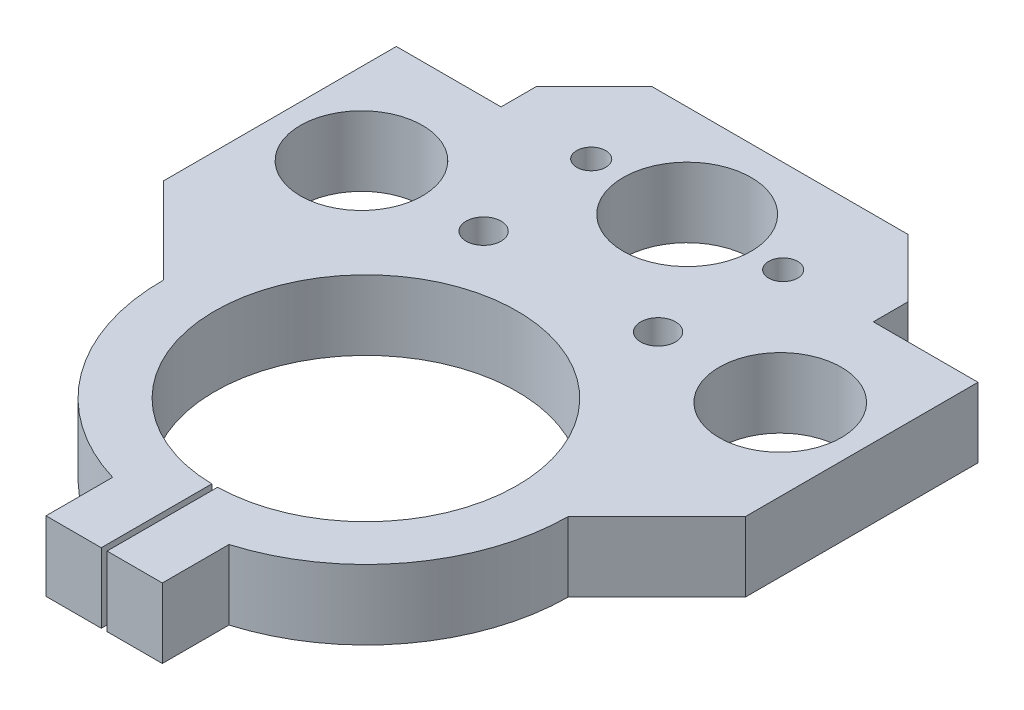
SolidWorks part; units mm, degrees
material "Beech"
ref_plane "Front Plane" through (0, 0, 0) normal (0, 0, 1) x (1, 0, 0)
ref_plane "Top Plane" through (0, 0, 0) normal (0, 1, 0) x (1, 0, 0)
ref_plane "Right Plane" through (0, 0, 0) normal (1, 0, 0) x (0, 0, -1)
sketch "Sketch1" plane through (0, 0, 0) normal (0, 1, 0) x (1, 0, 0)
  line L0 (-78.2213, 0) -> (76.4691, 0) construction
  line L1 (-50, 50) -> (50, 50)
  line L2 (-50, 50) -> (-50, -50)
  line L3 (-50, -50) -> (50, -50)
  line L4 (50, 50) -> (50, -50)
  line L5 (-50, 50) -> (50, -50) construction
  line L6 (-50, -50) -> (50, 50) construction
  line L7 (0, 33.1811) -> (0, -33.1904) construction
  circle A0 centre (0, 0) radius 11
  point P0 (0, 0)
  dimension "D2" = 22
  dimension "D1" = 100
  dimension "D7" = 100
extrude "Boss-Extrude1" add sketch "Sketch1" along normal blind 12
sketch "Sketch9" plane through (0, 12, 0) normal (0, 1, 0) x (1, 0, 0)
  line L0 (-50, -50) -> (-50, -100)
  line L1 (-50, -50) -> (50, -50)
  line L2 (50, -50) -> (50, -100)
  line L3 (50, -100) -> (-50, -100)
  dimension "D1" = 50
extrude "Boss-Extrude3" add sketch "Sketch9" against normal blind 12
sketch "Sketch4" plane through (0, 12, 0) normal (0, 1, 0) x (1, 0, 0)
  line L0 (-37.4627, -20) -> (37.4275, -20) construction
  circle A0 centre (-36, -20) radius 10.5
  circle A1 centre (36, -20) radius 10.5
  dimension "D2" = 21
  dimension "D3" = 21
  dimension "D4" = 36
  dimension "D5" = 72
  dimension "D1" = 20
extrude "Cut-Extrude3" cut sketch "Sketch4" against normal up to next
sketch "Sketch5" plane through (0, 12, 0) normal (0, 1, 0) x (1, 0, 0)
  line L0 (-50, 0) -> (-32, 0)
  line L1 (-50, 50) -> (-50, -100) construction
  line L2 (-32, 0) -> (-32, 16)
  line L3 (-32, 16) -> (32, 16)
  line L4 (32, 16) -> (32, 0)
  line L5 (32, 0) -> (50, 0)
  line L6 (50, -100) -> (50, 50) construction
  line L7 (50, 0) -> (50, 50)
  line L8 (50, 50) -> (-50, 50)
  line L9 (-50, 50) -> (-50, 0)
  dimension "D1" = 18
  dimension "D2" = 18
  dimension "D3" = 50
  dimension "D4" = 50
  dimension "D5" = 34
extrude "Cut-Extrude4" cut sketch "Sketch5" against normal up to next
sketch "Sketch6" plane through (0, 12, 0) normal (0, 1, 0) x (1, 0, 0)
  line L0 (0, -8.8019) -> (0, -112.6327) construction
  line L1 (-30.2744, -55) -> (29.8045, -55) construction
  circle A0 centre (-0.235, -55) radius 26
  circle A1 centre (-36, -20) radius 10.5 construction
  dimension "D1" = 52
  dimension "D2" = 35
extrude "Cut-Extrude5" cut sketch "Sketch6" against normal up to next
sketch "Sketch10" plane through (0, 12, 0) normal (0, 1, 0) x (1, 0, 0)
  line L0 (-0.235, -81) -> (-0.235, -100) construction
  line L1 (-10.235, -88.541) -> (-10.235, -100)
  line L2 (9.765, -88.541) -> (9.765, -100)
  line L3 (-10.235, -55) -> (-10.235, -122.2178) construction
  line L4 (9.765, -55) -> (9.765, -122.2178) construction
  line L5 (50, -40) -> (34.7642, -55.2358)
  line L6 (-50, 0) -> (-50, -100) construction
  line L7 (-50, -40) -> (-35.2342, -54.7658)
  line L8 (50, -100) -> (50, 0) construction
  line L9 (-50, -40) -> (-50, -100)
  line L10 (-50, -100) -> (-10.235, -100)
  line L11 (-50, -100) -> (50, -100) construction
  line L12 (9.765, -100) -> (50, -100)
  line L13 (50, -100) -> (50, -40)
  line L14 (-0.735, -80.9952) -> (-0.735, -100)
  line L15 (0.265, -80.9952) -> (0.265, -100)
  line L16 (0.265, -55) -> (0.265, -122.2178) construction
  line L17 (-0.235, -55) -> (-0.235, -122.2178) construction
  line L18 (-0.735, -55) -> (-0.735, -122.2178) construction
  line L19 (-0.735, -100) -> (0.265, -100)
  arc A0 (-35.2342, -54.7658) -> (-10.235, -88.541) centre (-0.235, -55) ccw
  circle A1 centre (-36, -20) radius 10.5 construction
  circle A2 centre (36, -20) radius 10.5 construction
  arc A3 (9.765, -88.541) -> (34.7642, -55.2358) centre (-0.235, -55) ccw
  circle A4 centre (-0.235, -55) radius 26 construction
  arc A5 (-0.735, -80.9952) -> (0.265, -80.9952) centre (-0.235, -55) ccw
  dimension "D1" = 70
  dimension "D4" = 20
  dimension "D5" = 20
  dimension "D8" = 45
  dimension "D9" = 45
  dimension "D2" = 10
  dimension "D3" = 10
  dimension "D6" = 0.5
  dimension "D7" = 0.5
extrude "Cut-Extrude6" cut sketch "Sketch10" against normal up to next
sketch "Sketch11" plane through (0, 12, 0) normal (0, 1, 0) x (1, 0, 0)
  line L0 (-24.0848, 0) -> (23.7988, 0) construction
  circle A0 centre (-16.5, 0) radius 2.5
  circle A1 centre (16.5, 0) radius 2.5
  circle A2 centre (0, 0) radius 11 construction
  dimension "D1" = 5
  dimension "D2" = 5
  dimension "D3" = 33
  dimension "D4" = 16.5
extrude "Cut-Extrude7" cut sketch "Sketch11" against normal up to next
chamfer "Chamfer1" distance 10 angle 45 2 edges at (-32, 6, -16) (32, 6, -16)
sketch "Sketch12" plane through (0, 12, 0) normal (0, 1, 0) x (1, 0, 0)
  line L0 (-36, -20) -> (36, -20) construction
  line L1 (0, -5.6783) -> (0, -40.549) construction
  circle A0 centre (15, -20) radius 3
  circle A1 centre (-15, -20) radius 3
  dimension "D1" = 6
  dimension "D2" = 6
  dimension "D3" = 30
  dimension "D4" = 15
extrude "Cut-Extrude8" cut sketch "Sketch12" against normal up to next
